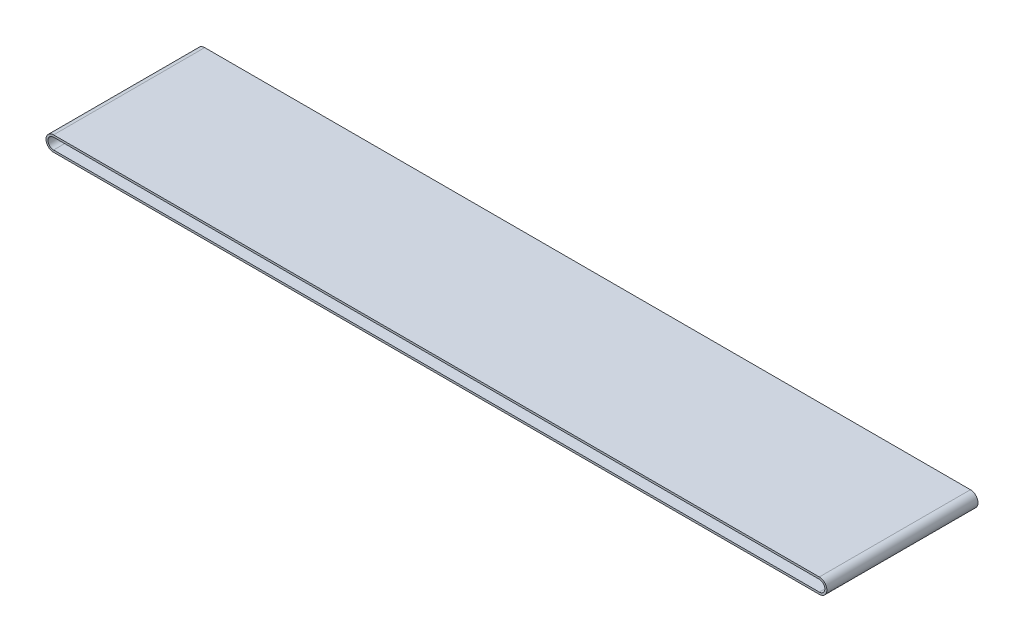
SolidWorks part; units mm, degrees
material "Rubber"
ref_plane "Front Plane" through (0, 0, 0) normal (0, 0, 1) x (1, 0, 0)
ref_plane "Top Plane" through (0, 0, 0) normal (0, 1, 0) x (1, 0, 0)
ref_plane "Right Plane" through (0, 0, 0) normal (1, 0, 0) x (0, 0, -1)
sketch "Sketch1" plane through (0, 0, 0) normal (0, 0, 1) x (1, 0, 0)
  line L0 (0, 38.1) -> (3860.8, 38.1)
  line L1 (0, -38.1) -> (3860.8, -38.1)
  line L2 (0, 27.94) -> (3860.8, 27.94)
  line L3 (0, -27.94) -> (3860.8, -27.94)
  arc A0 (0, 38.1) -> (0, -38.1) centre (0, 0) ccw
  arc A1 (3860.8, -38.1) -> (3860.8, 38.1) centre (3860.8, 0) ccw
  arc A2 (3860.8, -27.94) -> (3860.8, 27.94) centre (3860.8, 0) ccw
  arc A3 (0, 27.94) -> (0, -27.94) centre (0, 0) ccw
  dimension "D1" = 76.2
  dimension "D2" = 3937
  dimension "D3" = 10.16
extrude "Boss-Extrude1" add sketch "Sketch1" along normal mid plane 762
